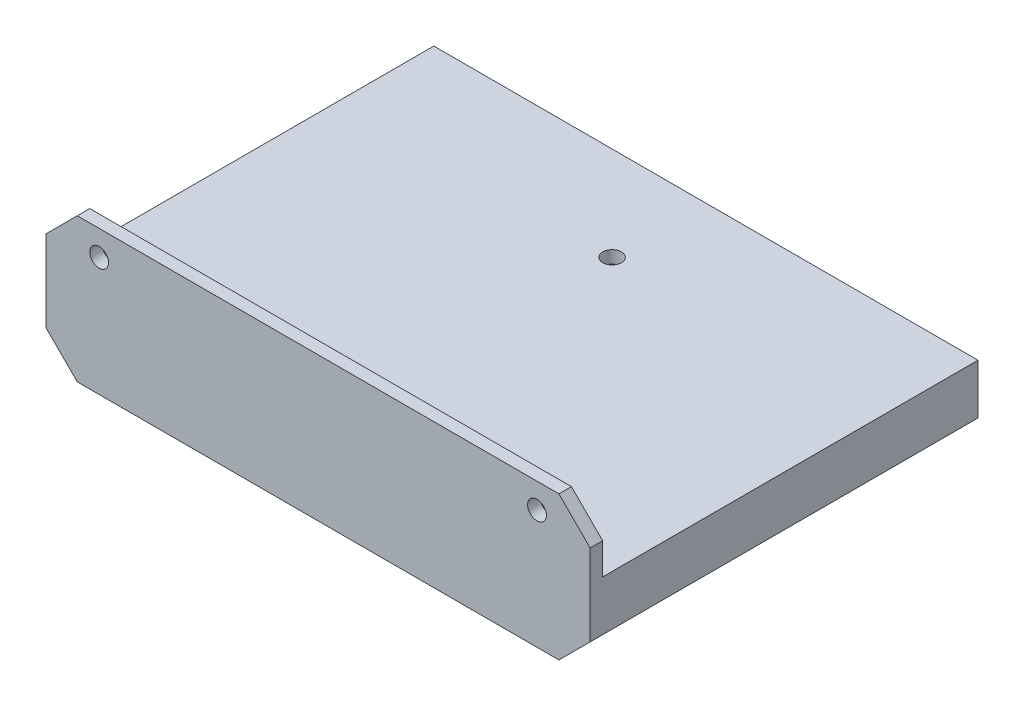
SolidWorks part; units mm, degrees
ref_plane "Спереди" through (0, 0, 0) normal (0, 0, 1) x (1, 0, 0)
ref_plane "Сверху" through (0, 0, 0) normal (0, 1, 0) x (1, 0, 0)
ref_plane "Справа" through (0, 0, 0) normal (1, 0, 0) x (0, 0, -1)
other "Configuration Table"
sketch "Эскиз1" plane through (0, 0, 0) normal (0, 0, 1) x (1, 0, 0)
  line L1 (30.5, 0) -> (38.5, 8)
  line L2 (38.5, 8) -> (-38.5, 8)
  line L3 (-38.5, 8) -> (-30.5, 0)
  line L4 (-30.5, 0) -> (-72.4513, 0) construction
  line L5 (30.5, 0) -> (43.5, 0)
  line L6 (-43.5, 13) -> (43.5, 13)
  line L7 (-43.5, 13) -> (-43.5, 0)
  line L8 (-43.5, 0) -> (-30.5, 0)
  line L9 (43.5, 13) -> (43.5, 0)
  point P3 (0, 8)
  point P4 (0, 0)
  dimension "D1" = 61
  dimension "D2" = 45
  dimension "D3" = 8
  dimension "D4" = 5
  dimension "D5" = 5
  dimension "D6" = 5
extrude "Бобышка-Вытянуть1" add sketch "Эскиз1" along normal blind 60
sketch "Эскиз2" plane through (0, 0, 60) normal (0, 0, 1) x (1, 0, 0)
  line L0 (43.5, 0) -> (43.5, 13) construction
  line L1 (-43.5, 0) -> (43.5, 0)
  line L2 (-43.5, 0) -> (-43.5, 23)
  line L3 (-43.5, 23) -> (43.5, 23)
  line L4 (43.5, 0) -> (43.5, 23)
  line L5 (43.5, 13) -> (-43.5, 13) construction
  dimension "D1" = 10
extrude "Бобышка-Вытянуть2" add sketch "Эскиз2" along normal blind 2
sketch "Эскиз3" plane through (0, 0, 62) normal (0, 0, 1) x (1, 0, 0)
  line L0 (0, 0) -> (0, 23) construction
  line L1 (-43.5, 0) -> (43.5, 0) construction
  line L2 (43.5, 23) -> (-43.5, 23) construction
  circle A0 centre (-35, 19) radius 1.5
  circle A1 centre (35, 19) radius 1.5
  dimension "D2" = 3
  dimension "D1" = 4
  dimension "D3" = 35
extrude "Вырез-Вытянуть1" cut sketch "Эскиз3" against normal up to surface (2 mm away) up to face at (0, 18, 60)
sketch "Эскиз4" plane through (0, 8, 0) normal (0, -1, 0) x (1, 0, 0)
  line L0 (0, 62) -> (0, 0) construction
  line L1 (-43.5, 62) -> (43.5, 62) construction
  line L2 (-38.5, 0) -> (38.5, 0) construction
  circle A0 centre (0, 15) radius 1.5
  dimension "D1" = 3
  dimension "D2" = 15
extrude "Вырез-Вытянуть2" cut sketch "Эскиз4" against normal up to surface (5 mm away) up to face at (0, 13, 30)
sketch "Эскиз5" plane through (0, 8, 0) normal (0, -1, 0) x (1, 0, 0)
  circle A0 centre (0, 15) radius 4
  dimension "D1" = 8
extrude "Вырез-Вытянуть3" cut sketch "Эскиз5" against normal blind 3
chamfer "Фаска1" distance 1 angle 45 3 edges at (34.5, 4, 0) (0, 8, 0) (-34.5, 4, 0)
chamfer "Фаска2" distance 5 angle 45 4 edges at (-43.5, 23, 61) (43.5, 23, 61) (43.5, 0, 31) (-43.5, 0, 31)
